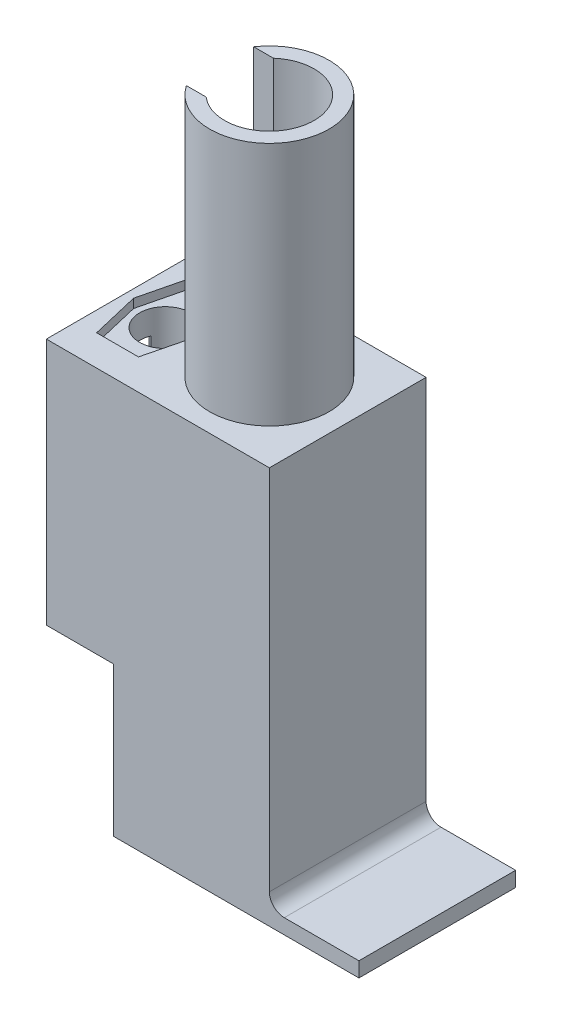
SolidWorks part; units mm, degrees
ref_plane "Front Plane" through (0, 0, 0) normal (0, 0, 1) x (1, 0, 0)
ref_plane "Top Plane" through (0, 0, 0) normal (0, 1, 0) x (1, 0, 0)
ref_plane "Right Plane" through (0, 0, 0) normal (1, 0, 0) x (0, 0, -1)
sketch "Sketch1" plane through (0, 0, 0) normal (0, 1, 0) x (1, 0, 0)
  line L1 (-37.35, 26.25) -> (37.35, 26.25)
  line L2 (-37.35, 26.25) -> (-37.35, -26.25)
  line L3 (-37.35, -26.25) -> (37.35, -26.25)
  line L4 (37.35, 26.25) -> (37.35, -26.25)
  line L5 (-37.35, 26.25) -> (37.35, -26.25) construction
  line L6 (-37.35, -26.25) -> (37.35, 26.25) construction
  point P0 (0, 0)
  dimension "D1" = 74.7
  dimension "D2" = 52.5
extrude "Boss-Extrude1" add sketch "Sketch1" along normal blind 83
sketch "Sketch4" plane through (0, 0, 0) normal (0, -1, 0) x (1, 0, 0)
  line L1 (37.35, -26.25) -> (-37.35, -26.25) construction
  line L2 (-10.15, 21.25) -> (32.35, 21.25)
  line L3 (-10.15, 21.25) -> (-10.15, -21.25)
  line L4 (-10.15, -21.25) -> (32.35, -21.25)
  line L5 (32.35, 21.25) -> (32.35, -21.25)
  line L6 (-10.15, 21.25) -> (32.35, -21.25) construction
  line L7 (-10.15, -21.25) -> (32.35, 21.25) construction
  line L8 (37.35, 26.25) -> (37.35, -26.25) construction
  point P2 (11.1, 0)
  dimension "D1" = 42.5
  dimension "D2" = 42.5
  dimension "D3" = 5
  dimension "D4" = 5
extrude "Cut-Extrude1" cut sketch "Sketch4" against normal blind 24
sketch "Sketch7" plane through (0, 0, 0) normal (0, -1, 0) x (1, 0, 0)
  line L0 (-37.35, 0) -> (-10.15, 0) construction
  line L1 (-37.35, -26.25) -> (-37.35, 26.25) construction
  line L2 (-10.15, 21.25) -> (-10.15, -21.25) construction
  circle A0 centre (-23.75, 0) radius 8.6
  dimension "D1" = 17.2
extrude "Cut-Extrude6" cut sketch "Sketch7" against normal blind 130
sketch "Sketch13" plane through (-37.35, 0, 0) normal (-1, 0, 0) x (0, 0, 1)
  line L0 (0, 83) -> (0, 0) construction
  line L1 (-26.25, 83) -> (26.25, 83) construction
  line L2 (-26.25, 41.5) -> (26.25, 41.5) construction
  line L3 (-26.25, 83) -> (-26.25, 0) construction
  line L4 (26.25, 83) -> (26.25, 0) construction
  line L6 (-22.75, 72) -> (22.75, 72)
  line L7 (-22.75, 72) -> (-22.75, 11)
  line L8 (-22.75, 11) -> (22.75, 11)
  line L9 (22.75, 72) -> (22.75, 11)
  line L10 (-22.75, 72) -> (22.75, 11) construction
  line L11 (-22.75, 11) -> (22.75, 72) construction
  point P11 (0, 41.5)
  dimension "D1" = 61
  dimension "D2" = 45.5
extrude "Cut-Extrude16" cut sketch "Sketch13" against normal blind 4.99 and the other way through all
sketch "Sketch15" plane through (-32.36, 0, 0) normal (-1, 0, 0) x (0, 0, 1)
  line L0 (0, 72) -> (0, 11) construction
  line L1 (22.75, 72) -> (-22.75, 72) construction
  line L2 (-22.75, 11) -> (22.75, 11) construction
  line L4 (-3.1929, 72) -> (3.1929, 72)
  line L5 (-3.1929, 72) -> (-3.1929, 11)
  line L6 (-3.1929, 11) -> (3.1929, 11)
  line L7 (3.1929, 72) -> (3.1929, 11)
  line L8 (-3.1929, 72) -> (3.1929, 11) construction
  line L9 (-3.1929, 11) -> (3.1929, 72) construction
  point P6 (0, 41.5)
extrude "Cut-Extrude17" cut sketch "Sketch15" against normal blind 1
sketch "Sketch18" plane through (0, 0, 0) normal (0, -1, 0) x (1, 0, 0)
  line L1 (-10.15, 21.25) -> (32.35, 21.25)
  line L2 (-10.15, 21.25) -> (-10.15, -21.25)
  line L3 (-10.15, -21.25) -> (32.35, -21.25)
  line L4 (32.35, 21.25) -> (32.35, -21.25)
extrude "Boss-Extrude2" add sketch "Sketch18" against normal blind 31
sketch "Sketch19" plane through (0, 0, 0) normal (0, -1, 0) x (1, 0, 0)
  line L0 (-37.35, 26.25) -> (37.35, 26.25) construction
  line L1 (-14.9, 26.25) -> (37.35, 26.25)
  line L2 (-14.9, 26.25) -> (-14.9, -26.25)
  line L3 (-14.9, -26.25) -> (37.35, -26.25)
  line L4 (37.35, 26.25) -> (37.35, -26.25)
  dimension "D1" = 52.25
extrude "Boss-Extrude3" add sketch "Sketch19" along normal blind 50
sketch "Sketch20" plane through (0, -50, 0) normal (0, -1, 0) x (1, 0, 0)
  line L0 (37.35, 26.25) -> (-14.9, 26.25) construction
  line L1 (-10.15, 21.25) -> (32.35, 21.25)
  line L2 (-10.15, 21.25) -> (-10.15, -21.25)
  line L3 (-10.15, -21.25) -> (32.35, -21.25)
  line L4 (32.35, 21.25) -> (32.35, -21.25)
  line L5 (-10.15, 21.25) -> (32.35, -21.25) construction
  line L6 (-10.15, -21.25) -> (32.35, 21.25) construction
  line L7 (37.35, -26.25) -> (37.35, 26.25) construction
  point P0 (11.1, 0)
  dimension "D1" = 42.5
  dimension "D2" = 42.5
  dimension "D3" = 5
  dimension "D4" = 5
extrude "Cut-Extrude19" cut sketch "Sketch20" against normal blind 23.5
sketch "Sketch21" plane through (37.35, 0, 0) normal (1, 0, 0) x (0, 0, -1)
  line L0 (-26.25, 83) -> (-26.25, -50) construction
  line L1 (-26.25, -45) -> (26.25, -45)
  line L2 (-26.25, -45) -> (-26.25, -50)
  line L3 (-26.25, -50) -> (26.25, -50)
  line L4 (26.25, -45) -> (26.25, -50)
  dimension "D1" = 5
extrude "Boss-Extrude4" add sketch "Sketch21" along normal blind 30
fillet "Fillet1" radius 5 1 edges at (37.35, -45, 0)
sketch "Sketch22" plane through (0, -26.5, 0) normal (0, -1, 0) x (1, 0, 0)
  line L0 (11.1, 21.25) -> (11.1, -21.25) construction
  line L1 (32.35, 21.25) -> (-10.15, 21.25) construction
  line L2 (-10.15, -21.25) -> (32.35, -21.25) construction
  line L3 (-10.15, 0) -> (32.35, 0) construction
  line L4 (-10.15, 21.25) -> (-10.15, -21.25) construction
  line L5 (32.35, -21.25) -> (32.35, 21.25) construction
  circle A0 centre (11.1, 0) radius 15
  dimension "D1" = 30
extrude "Cut-Extrude20" cut sketch "Sketch22" against normal blind 120
sketch "Sketch23" plane through (0, 83, 0) normal (0, 1, 0) x (1, 0, 0)
  line L0 (-16.75, 16) -> (-12.7885, -0.14)
  line L1 (-30.75, 16) -> (-16.75, 16)
  line L3 (-30.75, -16) -> (-16.75, -16)
  line L7 (-16.75, -16) -> (-12.7885, -0.14)
  line L8 (-30.75, 16) -> (-34.5965, 0.2355)
  line L9 (-30.75, -16) -> (-34.5965, 0.2355)
  point P0 (-23.75, 0)
  dimension "D1" = 32
  dimension "D2" = 14
extrude "Cut-Extrude21" cut sketch "Sketch23" against normal blind 3 contours L3 L7 L0 L1 L8 L9
sketch "Sketch24" plane through (0, 83, 0) normal (0, 1, 0) x (1, 0, 0)
  circle A0 centre (11.1, 0) radius 15
  circle A1 centre (11.1, 0) radius 20
  dimension "D1" = 40
extrude "Boss-Extrude5" add sketch "Sketch24" along normal blind 82
sketch "Sketch27" plane through (0, 165, 0) normal (0, 1, 0) x (1, 0, 0)
  line L1 (-5.4232, 11.2687) -> (1.1996, 11.2687)
  line L3 (-5.4232, -11.2687) -> (1.1996, -11.2687)
  arc A0 (1.1996, 11.2687) -> (1.1996, -11.2687) centre (11.1, 0) ccw
  arc A1 (-5.4232, 11.2687) -> (-5.4232, -11.2687) centre (11.1, 0) ccw
  point P0 (11.1, 0)
extrude "Cut-Extrude22" cut sketch "Sketch27" against normal blind 82
